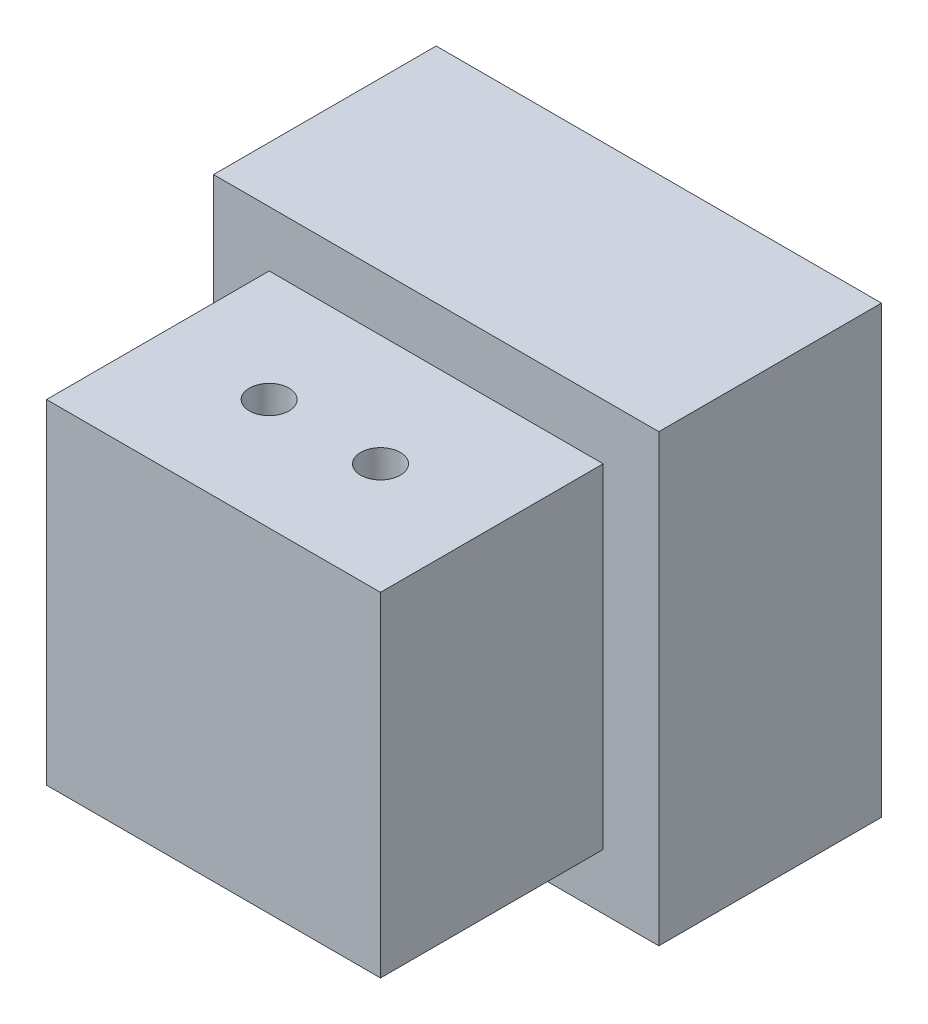
SolidWorks part; units mm, degrees
material "6061 Alloy"
ref_plane "Front" through (0, 0, 0) normal (0, 0, 1) x (1, 0, 0)
ref_plane "Top" through (0, 0, 0) normal (0, 1, 0) x (1, 0, 0)
ref_plane "Right" through (0, 0, 0) normal (1, 0, 0) x (0, 0, -1)
sketch "Sketch1" plane through (0, 0, 0) normal (0, 0, 1) x (1, 0, 0)
  line L1 (0, 0) -> (-25.4, 0) construction
  line L2 (0, 0) -> (0, 25.4) construction
  line L3 (0, 25.4) -> (-25.4, 25.4) construction
  line L4 (-25.4, 0) -> (-25.4, 25.4) construction
  line L5 (-3.175, 3.175) -> (-22.225, 3.175)
  line L6 (-3.175, 3.175) -> (-3.175, 22.225)
  line L7 (-3.175, 22.225) -> (-22.225, 22.225)
  line L8 (-22.225, 3.175) -> (-22.225, 22.225)
  dimension "D1" = 3.175
  dimension "D2" = 3.175
  dimension "D3" = 3.175
  dimension "D4" = 3.175
  dimension "D5" = 25.4
  dimension "D6" = 25.4
extrude "Boss-Extrude1" add sketch "Sketch1" along normal blind 12.7
sketch "Sketch2" plane through (0, 0, 0) normal (0, 0, -1) x (-1, 0, 0)
  line L0 (22.225, 22.225) -> (22.225, 3.175) construction
  line L1 (25.4, 0) -> (0, 0)
  line L2 (25.4, 0) -> (25.4, 25.4)
  line L3 (25.4, 25.4) -> (0, 25.4)
  line L4 (0, 0) -> (0, 25.4)
  line L5 (22.225, 3.175) -> (3.175, 3.175) construction
  line L6 (3.175, 3.175) -> (3.175, 22.225) construction
  line L7 (3.175, 22.225) -> (22.225, 22.225) construction
  dimension "D1" = 3.175
  dimension "D2" = 3.175
  dimension "D3" = 3.175
  dimension "D4" = 3.175
extrude "Boss-Extrude2" add sketch "Sketch2" along normal blind 12.7
sketch "Sketch3" plane through (0, 0, -12.7) normal (0, 0, -1) x (-1, 0, 0)
  line L0 (25.4, 25.4) -> (0, 25.4) construction
  line L1 (25.4, 0) -> (25.4, 25.4) construction
  circle A0 centre (12.7, 12.7) radius 9.525
  dimension "D1" = 12.7
  dimension "D2" = 12.7
  dimension "D3" = 19.05
extrude "Cut-Extrude3" cut sketch "Sketch3" against normal blind 10.16
ref_plane "Plane1" through (0, 25.4, 0) normal (0, -1, 0) x (-1, 0, 0)
hole_wizard "Tap Drill for #4-40 Tap1" positions "Sketch5" profile "Sketch6" hole size "#4-40" standard "ANSI Inch"
sketch "Sketch5" plane through (0, 22.225, 0) normal (0, 1, 0) x (1, 0, 0)
  line L0 (-3.175, 0) -> (-22.225, 0) construction
  line L3 (-22.225, -12.7) -> (-22.225, 0) construction
  point P0 (-9.525, -6.35)
  point P2 (-15.875, -6.35)
  point P23 (-15.3217, -12.7)
  point P24 (-13.1704, -12.7)
  point P25 (-17.876, -6.7827)
  dimension "D1" = 6.35
  dimension "D2" = 6.35
  dimension "D3" = 6.35
sketch "Sketch6" plane through (-9.525, 22.225, 6.35) normal (1, 0, 0) x (0, 0, 1)
  line L0 (0, 0) -> (0, 19.7282)
  line L1 (0, 19.7282) -> (1.1303, 19.049)
  line L2 (1.1303, 19.049) -> (1.1303, 0)
  line L5 (1.1303, 0) -> (0, 0)
  line L10 (0, 19.7282) -> (-1.1303, 19.049) construction
  line L11 (0, -6.35) -> (0, 107.95) construction
  dimension "Hole Dia." = 2.2606
  dimension "Hole Depth" = 19.049
  dimension "Drill Angle" = 118
